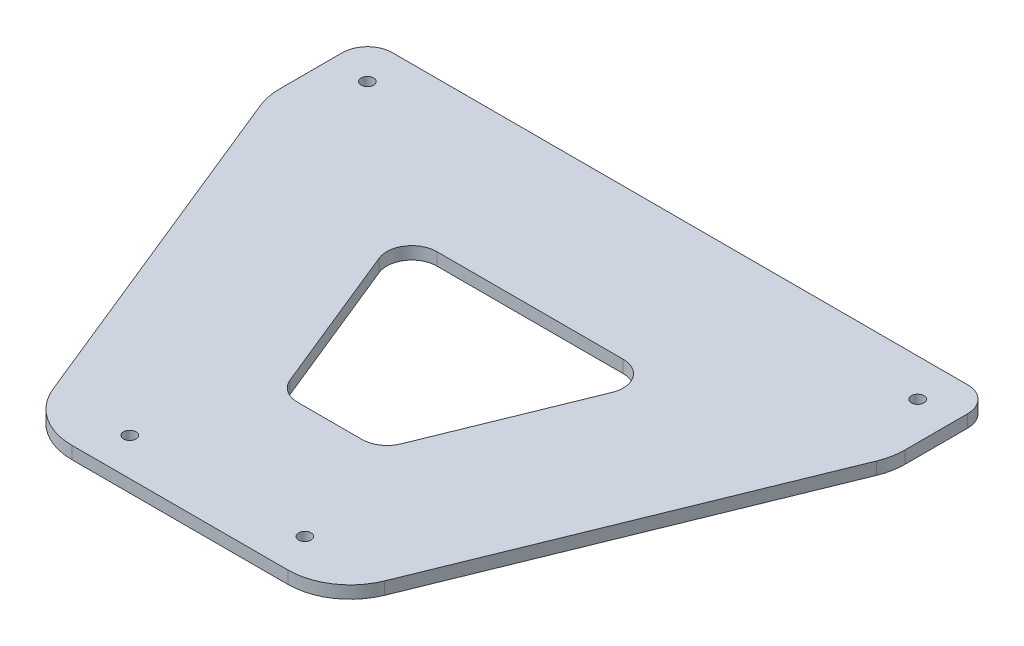
SolidWorks part; units mm, degrees
ref_plane "Plano frontal" through (0, 0, 0) normal (0, 0, 1) x (1, 0, 0)
ref_plane "Plano superior" through (0, 0, 0) normal (0, 1, 0) x (1, 0, 0)
ref_plane "Plano direito" through (0, 0, 0) normal (1, 0, 0) x (0, 0, -1)
sketch "Esboço1" plane through (0, 0, 0) normal (0, 1, 0) x (1, 0, 0)
  line L0 (25, -100) -> (85, -100) construction
  line L1 (68.172, -100) -> (-18.172, -100)
  line L2 (150, 64.8843) -> (150, 90)
  line L3 (140, 100) -> (-90, 100)
  line L4 (-100, 64.8843) -> (-100, 90)
  line L6 (150, 100) -> (146.7373, 97.3898) construction
  line L7 (85, -100) -> (-35, -100) construction
  line L8 (-100, 90) -> (-100, 60) construction
  line L9 (91.3337, -84.4094) -> (148.1617, 55.4749)
  line L10 (-96.7373, 97.3898) -> (-100, 100) construction
  line L12 (-41.3337, -84.4094) -> (-98.1617, 55.4749)
  line L13 (-100, 60) -> (150, 60) construction
  arc A0 (-100, 64.8843) -> (-98.1617, 55.4749) centre (-75, 64.8843) ccw
  arc A1 (150, 64.8843) -> (148.1617, 55.4749) centre (125, 64.8843) cw
  arc A2 (-90, 100) -> (-100, 90) centre (-90, 90) ccw
  arc A3 (150, 90) -> (140, 100) centre (140, 90) ccw
  arc A4 (91.3337, -84.4094) -> (68.172, -100) centre (68.172, -75) cw
  arc A5 (-18.172, -100) -> (-41.3337, -84.4094) centre (-18.172, -75) cw
  dimension "D1" = 25
  dimension "D2" = 250
extrude "Ressalto-extrusão1" add sketch "Esboço1" along normal blind 5
sketch "Esboço2" plane through (0, 5, 0) normal (0, 1, 0) x (1, 0, 0)
  line L0 (60, -85) -> (-10, -85) construction
  line L1 (150, 64.8843) -> (150, 90) construction
  line L2 (-100, 90) -> (-100, 64.8843) construction
  line L3 (-10, -85) -> (-100, -85) construction
  line L4 (-18.172, -100) -> (68.172, -100) construction
  line L5 (140, 100) -> (-90, 100) construction
  circle A0 centre (-85, 85) radius 2.5
  circle A1 centre (-10, -85) radius 2.5
  circle A2 centre (60, -85) radius 2.5
  circle A4 centre (135, 85) radius 2.5
  dimension "D1" = 5
  dimension "D9" = 15
  dimension "D2" = 70
  dimension "D3" = 15
  dimension "D4" = 15
  dimension "D5" = 15
  dimension "D6" = 15
  dimension "D7" = 90
  dimension "D10" = 15
extrude "Corte-extrusão1" cut sketch "Esboço2" against normal blind 5
sketch "Esboço3" plane through (0, 5, 0) normal (0, 1, 0) x (1, 0, 0)
  line L0 (-21.5213, 26.2362) -> (2.8537, -33.7638)
  line L1 (12.1184, -40) -> (37.8816, -40)
  line L2 (47.1463, -33.7638) -> (71.5213, 26.2362)
  line L4 (62.2566, 40) -> (-12.2566, 40)
  line L6 (-98.1617, 55.4749) -> (-41.3337, -84.4094)
  line L7 (-18.172, -100) -> (68.172, -100)
  line L8 (91.3337, -84.4094) -> (148.1617, 55.4749)
  line L9 (150, 64.8843) -> (150, 90)
  line L10 (140, 100) -> (-90, 100)
  line L11 (-100, 90) -> (-100, 64.8843)
  line L12 (-98.1617, 55.4749) -> (-41.3337, -84.4094)
  line L13 (-18.172, -100) -> (68.172, -100)
  line L14 (91.3337, -84.4094) -> (148.1617, 55.4749)
  line L15 (150, 64.8843) -> (150, 90)
  line L16 (140, 100) -> (-90, 100)
  line L17 (-100, 90) -> (-100, 64.8843)
  line L18 (-27.1128, 40) -> (5.3872, -40) construction
  line L19 (5.3872, -40) -> (44.6128, -40) construction
  line L20 (44.6128, -40) -> (77.1128, 40) construction
  line L21 (77.1128, 40) -> (-27.1128, 40) construction
  line L22 (-27.1128, 40) -> (-27.1128, 40) construction
  line L23 (77.1128, 40) -> (77.1128, 40) construction
  arc A0 (62.2566, 40) -> (71.5213, 26.2362) centre (62.2566, 30) cw
  arc A1 (47.1463, -33.7638) -> (37.8816, -40) centre (37.8816, -30) cw
  arc A2 (-12.2566, 40) -> (-21.5213, 26.2362) centre (-12.2566, 30) ccw
  arc A6 (-100, 64.8843) -> (-98.1617, 55.4749) centre (-75, 64.8843) ccw
  arc A7 (-41.3337, -84.4094) -> (-18.172, -100) centre (-18.172, -75) ccw
  arc A8 (68.172, -100) -> (91.3337, -84.4094) centre (68.172, -75) ccw
  arc A9 (148.1617, 55.4749) -> (150, 64.8843) centre (125, 64.8843) ccw
  arc A10 (150, 90) -> (140, 100) centre (140, 90) ccw
  arc A11 (-90, 100) -> (-100, 90) centre (-90, 90) ccw
  arc A12 (-100, 64.8843) -> (-98.1617, 55.4749) centre (-75, 64.8843) ccw
  arc A13 (-41.3337, -84.4094) -> (-18.172, -100) centre (-18.172, -75) ccw
  arc A14 (68.172, -100) -> (91.3337, -84.4094) centre (68.172, -75) ccw
  arc A15 (148.1617, 55.4749) -> (150, 64.8843) centre (125, 64.8843) ccw
  arc A16 (150, 90) -> (140, 100) centre (140, 90) ccw
  arc A17 (-90, 100) -> (-100, 90) centre (-90, 90) ccw
  arc A18 (2.8537, -33.7638) -> (12.1184, -40) centre (12.1184, -30) ccw
  arc A19 (5.3872, -40) -> (5.3872, -40) centre (5.3872, -40) ccw construction
  arc A20 (44.6128, -40) -> (44.6128, -40) centre (44.6128, -40) ccw construction
  arc A21 (-27.1128, 40) -> (-27.1128, 40) centre (-27.1128, 40) ccw construction
  arc A22 (-27.1128, 40) -> (-27.1128, 40) centre (-27.1128, 40) ccw construction
  arc A23 (77.1128, 40) -> (77.1128, 40) centre (77.1128, 40) ccw construction
  arc A24 (77.1128, 40) -> (77.1128, 40) centre (77.1128, 40) ccw construction
  dimension "D3" = 10
  dimension "D1" = 0
  dimension "D2" = 60
extrude "Corte-extrusão2" cut sketch "Esboço3" against normal blind 10 contours A0 L2 A1 L1 A18 L0 A2 L4
